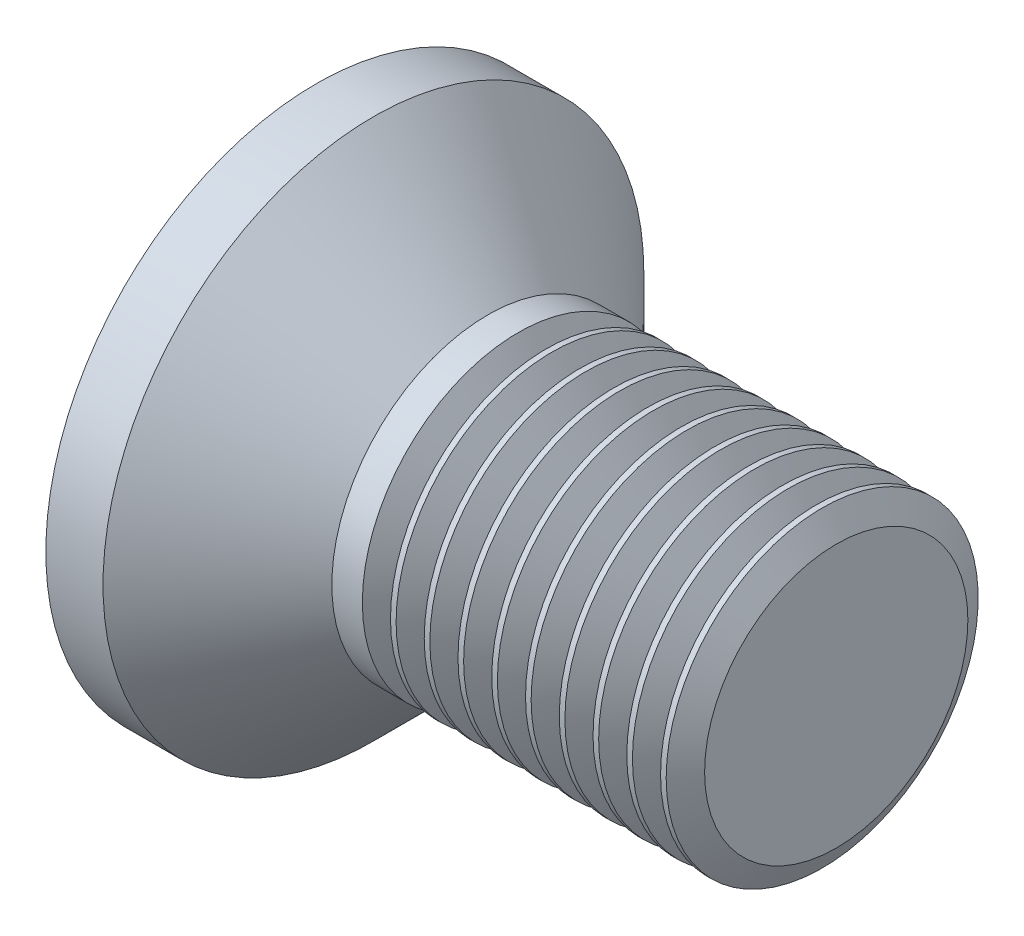
SolidWorks part; units mm, degrees
ref_plane "Front" through (0, 0, 0) normal (0, 0, 1) x (1, 0, 0)
ref_plane "Top" through (0, 0, 0) normal (0, 1, 0) x (1, 0, 0)
ref_plane "Right" through (0, 0, 0) normal (1, 0, 0) x (0, 0, -1)
other "Configuration Table"
sketch "Sketch1" plane through (0, 0, 0) normal (0, 0, 1) x (1, 0, 0)
  line L0 (5, 1.5) -> (2.65, 1.5)
  line L1 (2.65, 1.5) -> (1.65, 1.5)
  line L2 (1.65, 1.5) -> (0.55, 2.6)
  line L3 (0.55, 2.6) -> (0, 2.6)
  line L4 (5, 1.5) -> (5, 0)
  line L5 (4.5158, 0) -> (-89.8219, 0) construction
  line L6 (5, 0) -> (0, 0)
  line L7 (0, 2.6) -> (0, 0)
  dimension "d" = 3
  dimension "D1" = 45
  dimension "dk" = 5.2
  dimension "k" = 1.65
  dimension "l" = 5
  dimension "a" = 1
revolve "Base" add sketch "Sketch1" angle 360 about L5
cosmetic thread "ThreadCosmetic1" [suppressed] parameters "bb"=3.35, "THD_MINOR"=2.459
sketch "Sketch6" plane through (0, 0, 0) normal (1, 0, 0) x (0, 0, -1)
  line L0 (-1.9271, 0) -> (2.0512, 0) construction
  line L1 (0, 1.8651) -> (0, -2.0207) construction
  line L2 (0.32, 0.32) -> (0.32, 1.6)
  line L3 (0.32, 1.6) -> (-0.32, 1.6)
  line L4 (-0.32, 0.32) -> (-0.32, 1.6)
  line L5 (0.32, 0.32) -> (1.6, 0.32)
  line L6 (1.6, 0.32) -> (1.6, -0.32)
  line L7 (-1.6, 0.32) -> (-1.6, -0.32)
  line L8 (-0.32, 0.32) -> (-1.6, 0.32)
  line L9 (-0.32, -0.32) -> (-1.6, -0.32)
  line L10 (0.32, -0.32) -> (1.6, -0.32)
  line L11 (-0.32, -0.32) -> (-0.32, -1.6)
  line L12 (0.32, -1.6) -> (-0.32, -1.6)
  line L13 (0.32, -0.32) -> (0.32, -1.6)
  point P16 (-1.6, 0)
  point P17 (1.6, 0)
extrude "CrossRecess" cut sketch "Sketch6" along normal blind 0.825
draft "Draft9" type of draft neutral plane draft angle 30 faces to draft 4 face at (0.4125, 1.6, 0) face at (0.4125, 0, 1.6) face at (0.4125, -1.6, 0) face at (0.4125, 0, -1.6) neutral plane through (0, 2.6, 0) neutral plane normal (-1, 0, 0) parameters "D1"=30
fillet "Fillet5" radius 0.3 4 edges at (0.4125, -0.32, -0.32) (0.4125, 0.32, -0.32) (0.4125, 0.32, 0.32) (0.4125, -0.32, 0.32)
sketch "Sketch7" plane through (0, 0, 0) normal (1, 0, 0) x (0, 0, -1)
  line L0 (-2.0126, 0) -> (1.9757, 0) construction
  line L1 (0, 1.9314) -> (0, -2.0126) construction
  line L2 (0, 0) -> (1.5555, 1.5555) construction
  line L3 (0, 0.4782) -> (1.1314, 1.1314)
  line L4 (-1.5402, 1.5402) -> (0, 0) construction
  line L5 (0.4782, 0) -> (1.1314, 1.1314)
  line L6 (0, -0.4782) -> (1.1314, -1.1314)
  line L7 (0.4782, 0) -> (1.1314, -1.1314)
  line L8 (-0.4782, 0) -> (-1.1314, -1.1314)
  line L9 (0, -0.4782) -> (-1.1314, -1.1314)
  line L10 (-0.4782, 0) -> (-1.1314, 1.1314)
  line L11 (0, 0.4782) -> (-1.1314, 1.1314)
  dimension "D3" = 15
  dimension "m" = 3.2
extrude "Cut-Extrude3" [suppressed] cut sketch "Sketch7" along normal blind 10 draft 20
sketch "Sketch8" plane through (0, 0, 0) normal (0, 0, 1) x (1, 0, 0)
  line L0 (-20, 1.7705) -> (-21.25, 1.5)
  line L1 (-21.25, 1.5) -> (1.65, 1.5)
  line L3 (5, -1.5) -> (5, 1.5) construction
  line L6 (1.65, 1.5) -> (1.65, 6.5)
  line L7 (1.65, 6.5) -> (-20, 6.5)
  line L8 (-20, 6.5) -> (-20, 1.7705)
  line L9 (62.4753, 0.2705) -> (52.9594, 0.2705) construction
  dimension "D1" = 5
  dimension "x" = 1.25
  dimension "d" = 3
  dimension "THD_MINOR" = 2.459
  dimension "b" = 25
sketch "Sketch9" plane through (0, 0, 0) normal (0, 0, 1) x (1, 0, 0)
  line L0 (5, 1.2657) -> (5.1353, 1.5)
  line L1 (5.1353, 1.5) -> (5.1353, 1.7705)
  line L2 (5.1353, 1.7705) -> (4.8647, 1.7705)
  line L3 (4.8647, 1.7705) -> (4.8647, 1.5)
  line L4 (4.8647, 1.5) -> (5, 1.2657)
  line L5 (0, 0) -> (73.843, 0) construction
  line L6 (5, -1.5) -> (5, 1.5) construction
  dimension "D1" = 3
  dimension "D2" = 0.2705
revolve "Cut-Revolve10" cut sketch "Sketch9" angle 360 about L5
pattern_linear "LPattern10" count 10 spacing 0.3246 along (-1, 0, 0) of "Cut-Revolve10"
equation "\"D1@Sketch6\" = \"m@Sketch6\" / 5"
equation "\"D1@CrossRecess\" = \"k@Sketch1\" / 2"
equation "\"D1@Sketch9\" = \"d@Sketch1\""
equation "\"D2@Sketch9\" =  ( \"d@Sketch1\" - \"THD_MINOR@ThreadCosmetic1\" )  / 2"
equation "\"D3@LPattern10\" = \"D2@Sketch9\" * 1.2"
equation "\"D1@LPattern10\" = \"bb@ThreadCosmetic1\" / \"D3@LPattern10\" "
